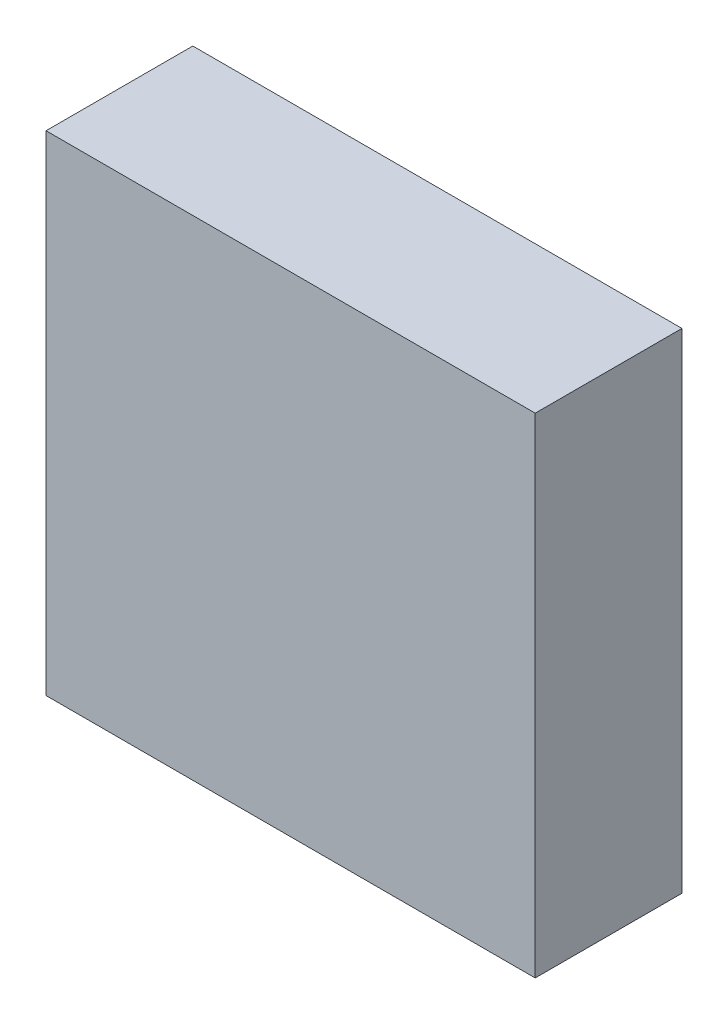
SolidWorks part; units mm, degrees
ref_plane "Спереди" through (0, 0, 0) normal (0, 0, 1) x (1, 0, 0)
ref_plane "Сверху" through (0, 0, 0) normal (0, 1, 0) x (1, 0, 0)
ref_plane "Справа" through (0, 0, 0) normal (1, 0, 0) x (0, 0, -1)
sketch "Эскиз1" plane through (0, 0, 0) normal (0, 0, 1) x (1, 0, 0)
  line L1 (-50, -50) -> (50, -50)
  line L2 (-50, -50) -> (-50, 50)
  line L3 (-50, 50) -> (50, 50)
  line L4 (50, -50) -> (50, 50)
  line L5 (-50, -50) -> (50, 50) construction
  line L6 (-50, 50) -> (50, -50) construction
  point P0 (0, 0)
  dimension "D1" = 100
  dimension "D2" = 100
extrude "Бобышка-Вытянуть1" add sketch "Эскиз1" along normal blind 30
